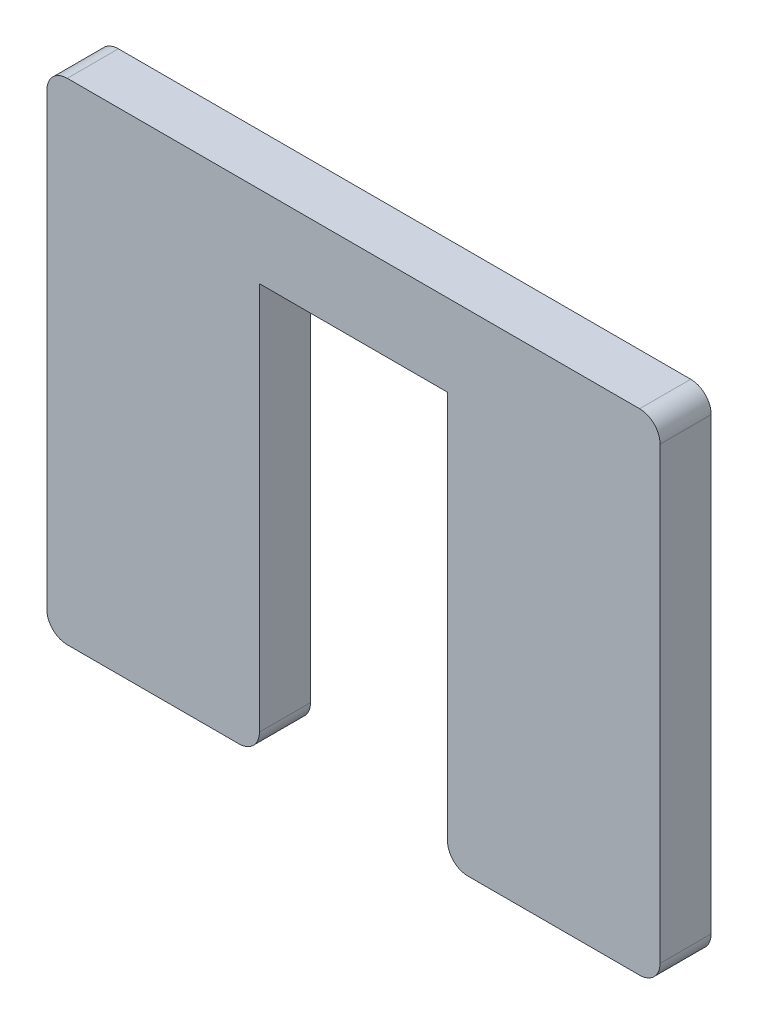
SolidWorks part; units mm, degrees
ref_plane "前视基准面" through (0, 0, 0) normal (0, 0, 1) x (1, 0, 0)
ref_plane "上视基准面" through (0, 0, 0) normal (0, 1, 0) x (1, 0, 0)
ref_plane "右视基准面" through (0, 0, 0) normal (1, 0, 0) x (0, 0, -1)
sketch "草图1" plane through (0, 0, 0) normal (0, 0, 1) x (1, 0, 0)
  line L0 (0, 24) -> (0, -22) construction
  line L1 (-30, 24) -> (30, 24)
  line L2 (-30, 24) -> (-30, -24)
  line L3 (-30, -24) -> (-9.2, -24)
  line L4 (30, 24) -> (30, -24)
  line L5 (-30, 24) -> (30, -24) construction
  line L6 (-30, -24) -> (30, 24) construction
  line L7 (9.2, -24) -> (30, -24)
  line L9 (-9.2, -24) -> (-9.2, 16)
  line L10 (-9.2, 16) -> (9.2, 16)
  line L11 (9.2, -24) -> (9.2, 16)
  point P0 (0, 0)
  dimension "D1" = 60
  dimension "D2" = 48
  dimension "D3" = 18.4
  dimension "D4" = 9.2
  dimension "D5" = 40
extrude "凸台-拉伸1" add sketch "草图1" along normal blind 5
fillet "圆角1" radius 2 6 edges at (30, -24, 2.5) (9.2, -24, 2.5) (-9.2, -24, 2.5) (-30, -24, 2.5) (-30, 24, 2.5) (30, 24, 2.5)
